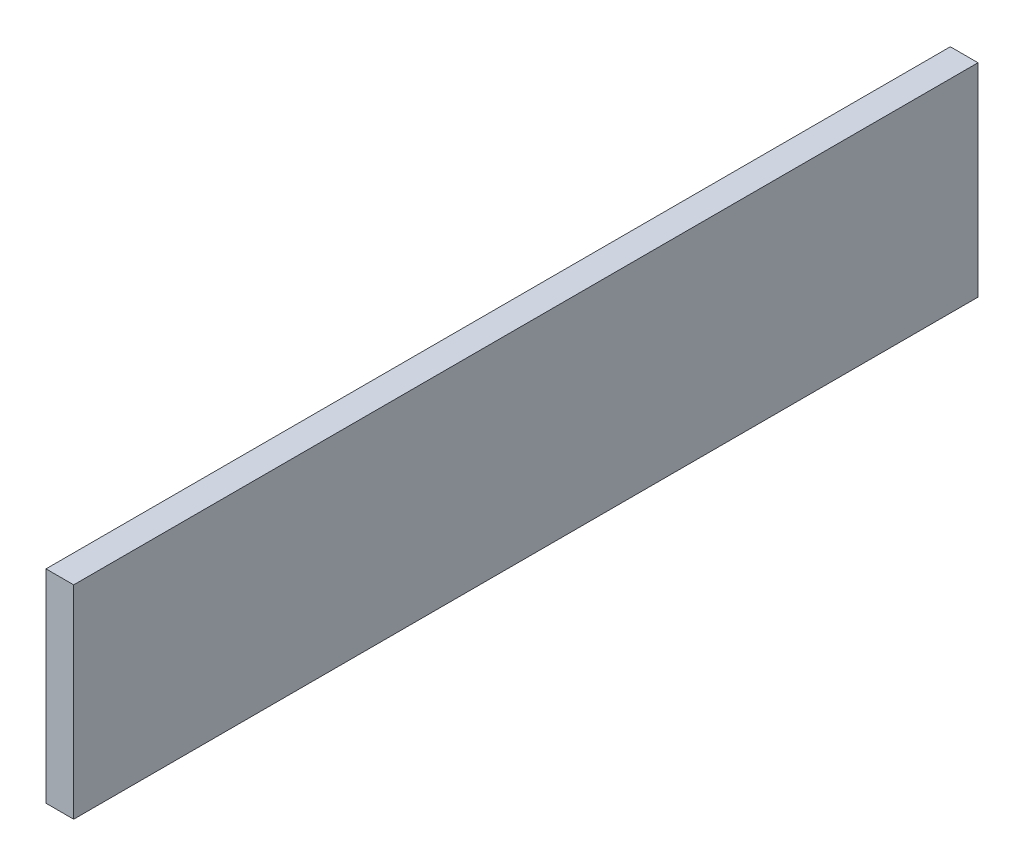
SolidWorks part; units mm, degrees
ref_plane "Front Plane" through (0, 0, 0) normal (0, 0, 1) x (1, 0, 0)
ref_plane "Top Plane" through (0, 0, 0) normal (0, 1, 0) x (1, 0, 0)
ref_plane "Right Plane" through (0, 0, 0) normal (1, 0, 0) x (0, 0, -1)
sketch "Sketch1" plane through (0, 0, 0) normal (1, 0, 0) x (0, 0, -1)
  line L1 (0, 0) -> (622.3, 0)
  line L2 (0, 0) -> (0, 139.7)
  line L3 (0, 139.7) -> (622.3, 139.7)
  line L4 (622.3, 0) -> (622.3, 139.7)
  dimension "D1" = 622.3
  dimension "D2" = 139.7
extrude "Boss-Extrude1" add sketch "Sketch1" along normal blind 19.05
